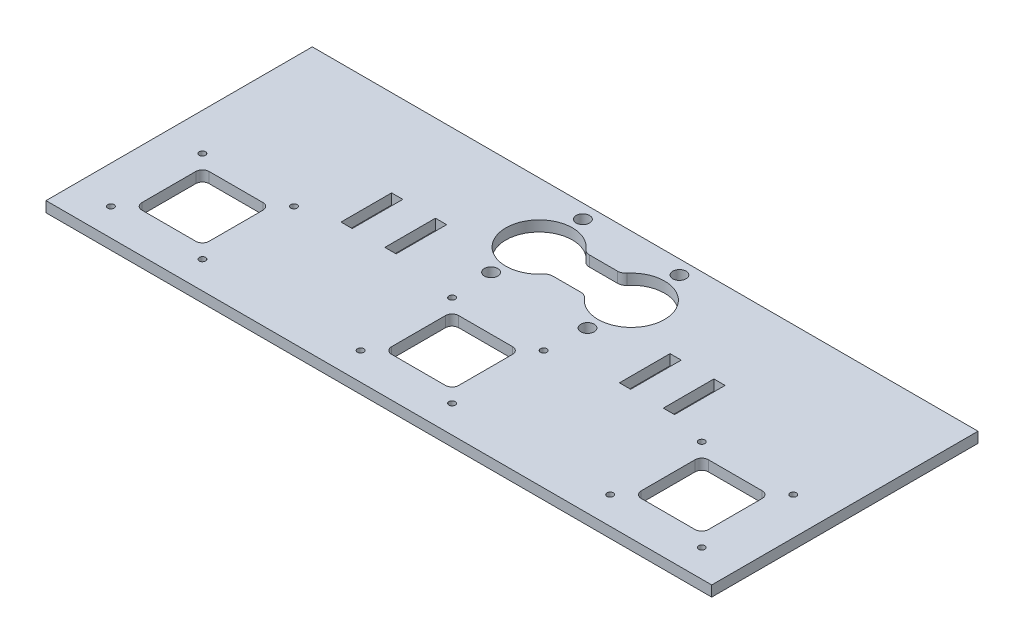
SolidWorks part; units mm, degrees
ref_plane "Front Plane" through (0, 0, 0) normal (0, 0, 1) x (1, 0, 0)
ref_plane "Top Plane" through (0, 0, 0) normal (0, 1, 0) x (1, 0, 0)
ref_plane "Right Plane" through (0, 0, 0) normal (1, 0, 0) x (0, 0, -1)
sketch "Sketch1" plane through (0, 0, 0) normal (0, 1, 0) x (1, 0, 0)
  line L1 (-100, 40) -> (100, 40)
  line L2 (-100, 40) -> (-100, -40)
  line L3 (-100, -40) -> (100, -40)
  line L4 (100, 40) -> (100, -40)
  line L5 (-100, 40) -> (100, -40) construction
  line L6 (-100, -40) -> (100, 40) construction
  point P0 (0, 0)
  dimension "D1" = 200
  dimension "D2" = 80
extrude "Boss-Extrude1" add sketch "Sketch1" along normal blind 3.175
sketch "Sketch3" plane through (0, 3.175, 0) normal (0, 1, 0) x (1, 0, 0)
  line L4 (100, -40) -> (100, 40)
  line L5 (100, 40) -> (-100, 40)
  line L6 (-100, 40) -> (-100, -40)
  line L7 (-100, -40) -> (100, -40)
  line L8 (100, -40) -> (100, 40) construction
  line L9 (100, 40) -> (-100, 40) construction
  line L10 (-100, 40) -> (-100, -40) construction
  line L11 (-100, -40) -> (100, -40) construction
  line L12 (83.085, -9.915) -> (66.915, -9.915) construction
  line L13 (83.085, -26.085) -> (83.085, -9.915) construction
  line L14 (66.915, -9.915) -> (66.915, -26.085) construction
  line L15 (66.915, -26.085) -> (83.085, -26.085) construction
  line L16 (-66.915, -9.915) -> (-83.085, -9.915) construction
  line L17 (-83.085, -9.915) -> (-83.085, -26.085) construction
  line L18 (-66.915, -26.085) -> (-66.915, -9.915) construction
  line L19 (-83.085, -26.085) -> (-66.915, -26.085) construction
  line L20 (8.085, -9.915) -> (-8.085, -9.915) construction
  line L21 (8.085, -26.085) -> (8.085, -9.915) construction
  line L22 (-8.085, -26.085) -> (8.085, -26.085) construction
  line L23 (-8.085, -9.915) -> (-8.085, -26.085) construction
  line L24 (4.2453, 27) -> (-4.2453, 27) construction
  line L25 (-4.2453, 17) -> (4.2453, 17) construction
  line L26 (83.085, -9.915) -> (66.915, -9.915) construction
  line L27 (83.085, -26.085) -> (83.085, -9.915) construction
  line L28 (66.915, -9.915) -> (66.915, -26.085) construction
  line L29 (66.915, -26.085) -> (83.085, -26.085) construction
  line L30 (-66.915, -9.915) -> (-83.085, -9.915) construction
  line L31 (-83.085, -9.915) -> (-83.085, -26.085) construction
  line L32 (-66.915, -26.085) -> (-66.915, -9.915) construction
  line L33 (-83.085, -26.085) -> (-66.915, -26.085) construction
  line L34 (8.085, -9.915) -> (-8.085, -9.915) construction
  line L35 (8.085, -26.085) -> (8.085, -9.915) construction
  line L36 (-8.085, -26.085) -> (8.085, -26.085) construction
  line L37 (-8.085, -9.915) -> (-8.085, -26.085) construction
  line L38 (4.2453, 27) -> (-4.2453, 27) construction
  line L39 (-4.2453, 17) -> (4.2453, 17) construction
  line L40 (85.085, -7.915) -> (64.915, -7.915)
  line L41 (64.915, -7.915) -> (64.915, -28.085)
  line L42 (64.915, -28.085) -> (85.085, -28.085)
  line L43 (85.085, -28.085) -> (85.085, -7.915)
  line L44 (-64.915, -7.915) -> (-85.085, -7.915)
  line L45 (-85.085, -7.915) -> (-85.085, -28.085)
  line L46 (-85.085, -28.085) -> (-64.915, -28.085)
  line L47 (-64.915, -28.085) -> (-64.915, -7.915)
  line L48 (10.085, -7.915) -> (-10.085, -7.915)
  line L49 (-10.085, -7.915) -> (-10.085, -28.085)
  line L50 (-10.085, -28.085) -> (10.085, -28.085)
  line L51 (10.085, -28.085) -> (10.085, -7.915)
  line L52 (4.2453, 27.5) -> (-4.2453, 27.5)
  line L53 (-4.2453, 16.5) -> (4.2453, 16.5)
  arc A0 (-6.5504, 28.08) -> (-4.2453, 27) centre (-4.2453, 30) ccw construction
  arc A1 (4.2453, 27) -> (6.5504, 28.08) centre (4.2453, 30) ccw construction
  arc A2 (6.5504, 15.92) -> (6.5504, 28.08) centre (13.85, 22) ccw construction
  arc A3 (6.5504, 15.92) -> (4.2453, 17) centre (4.2453, 14) ccw construction
  arc A4 (-4.2453, 17) -> (-6.5504, 15.92) centre (-4.2453, 14) ccw construction
  arc A5 (-6.5504, 28.08) -> (-6.5504, 15.92) centre (-13.85, 22) ccw construction
  arc A6 (-6.5504, 28.08) -> (-4.2453, 27) centre (-4.2453, 30) ccw construction
  arc A7 (4.2453, 27) -> (6.5504, 28.08) centre (4.2453, 30) ccw construction
  arc A8 (6.5504, 15.92) -> (6.5504, 28.08) centre (13.85, 22) ccw construction
  arc A9 (6.5504, 15.92) -> (4.2453, 17) centre (4.2453, 14) ccw construction
  arc A10 (-4.2453, 17) -> (-6.5504, 15.92) centre (-4.2453, 14) ccw construction
  arc A11 (-6.5504, 28.08) -> (-6.5504, 15.92) centre (-13.85, 22) ccw construction
  arc A12 (-6.1663, 28.4) -> (-4.2453, 27.5) centre (-4.2453, 30) ccw
  arc A13 (-6.1663, 28.4) -> (-6.1663, 15.6) centre (-13.85, 22) ccw
  arc A14 (-4.2453, 16.5) -> (-6.1663, 15.6) centre (-4.2453, 14) ccw
  arc A15 (6.1663, 15.6) -> (4.2453, 16.5) centre (4.2453, 14) ccw
  arc A16 (6.1663, 15.6) -> (6.1663, 28.4) centre (13.85, 22) ccw
  arc A17 (4.2453, 27.5) -> (6.1663, 28.4) centre (4.2453, 30) ccw
  point P42 (0, 0)
  dimension "D1" = 0
  dimension "D2" = 2
  dimension "D3" = 0.5
extrude "Cut-Extrude2" cut sketch "Sketch3" against normal through all
sketch "Sketch5" plane through (0, 0, 0) normal (0, -1, 0) x (1, 0, 0)
  circle A0 centre (14.5, -8.2) radius 2 construction
  circle A1 centre (-14.5, -8.2) radius 2 construction
  circle A2 centre (14.5, -35.8) radius 2 construction
  circle A3 centre (-14.5, -35.8) radius 2 construction
  circle A4 centre (14.5, -8.2) radius 2
  circle A5 centre (-14.5, -8.2) radius 2
  circle A6 centre (14.5, -35.8) radius 2
  circle A7 centre (-14.5, -35.8) radius 2
extrude "Cut-Extrude3" cut sketch "Sketch5" against normal through all
sketch "Sketch6" plane through (0, 0, 0) normal (0, -1, 0) x (1, 0, 0)
  circle A0 centre (-61.25, 4.25) radius 0.95 construction
  circle A1 centre (13.75, 4.25) radius 0.95 construction
  circle A2 centre (-88.75, 4.25) radius 0.95 construction
  circle A3 centre (-61.25, 31.75) radius 0.95 construction
  circle A4 centre (-13.75, 4.25) radius 0.95 construction
  circle A5 centre (-13.75, 31.75) radius 0.95 construction
  circle A6 centre (13.75, 31.75) radius 0.95 construction
  circle A7 centre (88.75, 31.75) radius 0.95 construction
  circle A8 centre (61.25, 31.75) radius 0.95 construction
  circle A9 centre (61.25, 4.25) radius 0.95 construction
  circle A10 centre (88.75, 4.25) radius 0.95 construction
  circle A11 centre (-61.25, 4.25) radius 0.95
  circle A12 centre (13.75, 4.25) radius 0.95
  circle A13 centre (-88.75, 4.25) radius 0.95
  circle A14 centre (-61.25, 31.75) radius 0.95
  circle A15 centre (-13.75, 4.25) radius 0.95
  circle A16 centre (-13.75, 31.75) radius 0.95
  circle A17 centre (13.75, 31.75) radius 0.95
  circle A18 centre (88.75, 31.75) radius 0.95
  circle A19 centre (61.25, 31.75) radius 0.95
  circle A20 centre (61.25, 4.25) radius 0.95
  circle A21 centre (88.75, 4.25) radius 0.95
  circle A22 centre (-88.75, 31.75) radius 0.95 construction
  circle A23 centre (-88.75, 31.75) radius 0.95
extrude "Cut-Extrude4" cut sketch "Sketch6" against normal through all
sketch "Sketch7" plane through (0, 3.175, 0) normal (0, 1, 0) x (1, 0, 0)
  line L0 (-50, 13.825) -> (-50, 12.825) construction
  line L1 (-46.825, 12.825) -> (-46.825, 13.825) construction
  line L2 (-46.825, 13.825) -> (-50, 13.825) construction
  line L3 (-50, 12.825) -> (-50, -0.175) construction
  line L4 (-46.825, -0.175) -> (-46.825, 12.825) construction
  line L5 (-50, -0.175) -> (-50, -1.175) construction
  line L6 (-50, -1.175) -> (-46.825, -1.175) construction
  line L7 (-46.825, -1.175) -> (-46.825, -0.175) construction
  line L8 (-36.825, -0.175) -> (-36.825, -1.175) construction
  line L9 (-36.825, -1.175) -> (-33.65, -1.175) construction
  line L10 (-33.65, -1.175) -> (-33.65, -0.175) construction
  line L11 (-36.825, 12.825) -> (-36.825, -0.175) construction
  line L12 (-33.65, -0.175) -> (-33.65, 12.825) construction
  line L13 (-36.825, 13.825) -> (-36.825, 12.825) construction
  line L14 (-33.65, 12.825) -> (-33.65, 13.825) construction
  line L15 (-33.65, 13.825) -> (-36.825, 13.825) construction
  line L16 (33.65, 13.825) -> (33.65, 12.825) construction
  line L17 (36.825, 12.825) -> (36.825, 13.825) construction
  line L18 (36.825, 13.825) -> (33.65, 13.825) construction
  line L19 (33.65, 12.825) -> (33.65, -0.175) construction
  line L20 (36.825, -0.175) -> (36.825, 12.825) construction
  line L21 (33.65, -0.175) -> (33.65, -1.175) construction
  line L22 (33.65, -1.175) -> (36.825, -1.175) construction
  line L23 (36.825, -1.175) -> (36.825, -0.175) construction
  line L24 (46.825, -0.175) -> (46.825, -1.175) construction
  line L25 (46.825, -1.175) -> (50, -1.175) construction
  line L26 (50, -1.175) -> (50, -0.175) construction
  line L27 (46.825, 12.825) -> (46.825, -0.175) construction
  line L28 (50, -0.175) -> (50, 12.825) construction
  line L29 (46.825, 13.825) -> (46.825, 12.825) construction
  line L30 (50, 12.825) -> (50, 13.825) construction
  line L31 (50, 13.825) -> (46.825, 13.825) construction
  line L32 (-50, 13.825) -> (-50, 12.825) construction
  line L33 (-46.825, 12.825) -> (-46.825, 13.825) construction
  line L34 (-46.825, 13.825) -> (-50, 13.825) construction
  line L35 (-50, 12.825) -> (-50, -0.175) construction
  line L36 (-46.825, -0.175) -> (-46.825, 12.825) construction
  line L37 (-50, -0.175) -> (-50, -1.175) construction
  line L38 (-50, -1.175) -> (-46.825, -1.175) construction
  line L39 (-46.825, -1.175) -> (-46.825, -0.175) construction
  line L40 (-36.825, -0.175) -> (-36.825, -1.175) construction
  line L41 (-36.825, -1.175) -> (-33.65, -1.175) construction
  line L42 (-33.65, -1.175) -> (-33.65, -0.175) construction
  line L43 (-36.825, 12.825) -> (-36.825, -0.175) construction
  line L44 (-33.65, -0.175) -> (-33.65, 12.825) construction
  line L45 (-36.825, 13.825) -> (-36.825, 12.825) construction
  line L46 (-33.65, 12.825) -> (-33.65, 13.825) construction
  line L47 (-33.65, 13.825) -> (-36.825, 13.825) construction
  line L48 (33.65, 13.825) -> (33.65, 12.825) construction
  line L49 (36.825, 12.825) -> (36.825, 13.825) construction
  line L50 (36.825, 13.825) -> (33.65, 13.825) construction
  line L51 (33.65, 12.825) -> (33.65, -0.175) construction
  line L52 (36.825, -0.175) -> (36.825, 12.825) construction
  line L53 (33.65, -0.175) -> (33.65, -1.175) construction
  line L54 (33.65, -1.175) -> (36.825, -1.175) construction
  line L55 (36.825, -1.175) -> (36.825, -0.175) construction
  line L56 (46.825, -0.175) -> (46.825, -1.175) construction
  line L57 (46.825, -1.175) -> (50, -1.175) construction
  line L58 (50, -1.175) -> (50, -0.175) construction
  line L59 (46.825, 12.825) -> (46.825, -0.175) construction
  line L60 (50, -0.175) -> (50, 12.825) construction
  line L61 (46.825, 13.825) -> (46.825, 12.825) construction
  line L62 (50, 12.825) -> (50, 13.825) construction
  line L63 (50, 13.825) -> (46.825, 13.825) construction
  line L64 (-50.1, 13.925) -> (-50.1, 12.825)
  line L65 (-50.1, 12.825) -> (-50.1, -0.175)
  line L66 (-50.1, -0.175) -> (-50.1, -1.275)
  line L67 (-50.1, -1.275) -> (-46.725, -1.275)
  line L68 (-46.725, -1.275) -> (-46.725, -0.175)
  line L69 (-46.725, -0.175) -> (-46.725, 12.825)
  line L70 (-46.725, 12.825) -> (-46.725, 13.925)
  line L71 (-46.725, 13.925) -> (-50.1, 13.925)
  line L72 (-36.925, -0.175) -> (-36.925, -1.275)
  line L73 (-36.925, -1.275) -> (-33.55, -1.275)
  line L74 (-33.55, -1.275) -> (-33.55, -0.175)
  line L75 (-33.55, -0.175) -> (-33.55, 12.825)
  line L76 (-33.55, 12.825) -> (-33.55, 13.925)
  line L77 (-33.55, 13.925) -> (-36.925, 13.925)
  line L78 (-36.925, 13.925) -> (-36.925, 12.825)
  line L79 (-36.925, 12.825) -> (-36.925, -0.175)
  line L80 (33.55, 13.925) -> (33.55, 12.825)
  line L81 (33.55, 12.825) -> (33.55, -0.175)
  line L82 (33.55, -0.175) -> (33.55, -1.275)
  line L83 (33.55, -1.275) -> (36.925, -1.275)
  line L84 (36.925, -1.275) -> (36.925, -0.175)
  line L85 (36.925, -0.175) -> (36.925, 12.825)
  line L86 (36.925, 12.825) -> (36.925, 13.925)
  line L87 (36.925, 13.925) -> (33.55, 13.925)
  line L88 (46.725, -0.175) -> (46.725, -1.275)
  line L89 (46.725, -1.275) -> (50.1, -1.275)
  line L90 (50.1, -1.275) -> (50.1, -0.175)
  line L91 (50.1, -0.175) -> (50.1, 12.825)
  line L92 (50.1, 12.825) -> (50.1, 13.925)
  line L93 (50.1, 13.925) -> (46.725, 13.925)
  line L94 (46.725, 13.925) -> (46.725, 12.825)
  line L95 (46.725, 12.825) -> (46.725, -0.175)
  dimension "D1" = 0.1
extrude "Cut-Extrude5" cut sketch "Sketch7" against normal through all
fillet "Fillet1" radius 2 12 edges at (85.085, 1.5875, 28.085) (64.915, 1.5875, 28.085) (64.915, 1.5875, 7.915) (85.085, 1.5875, 7.915) (10.085, 1.5875, 7.915) (-10.085, 1.5875, 7.915) (10.085, 1.5875, 28.085) (-10.085, 1.5875, 28.085) (-85.085, 1.5875, 28.085) (-64.915, 1.5875, 7.915) (-64.915, 1.5875, 28.085) (-85.085, 1.5875, 7.915)
